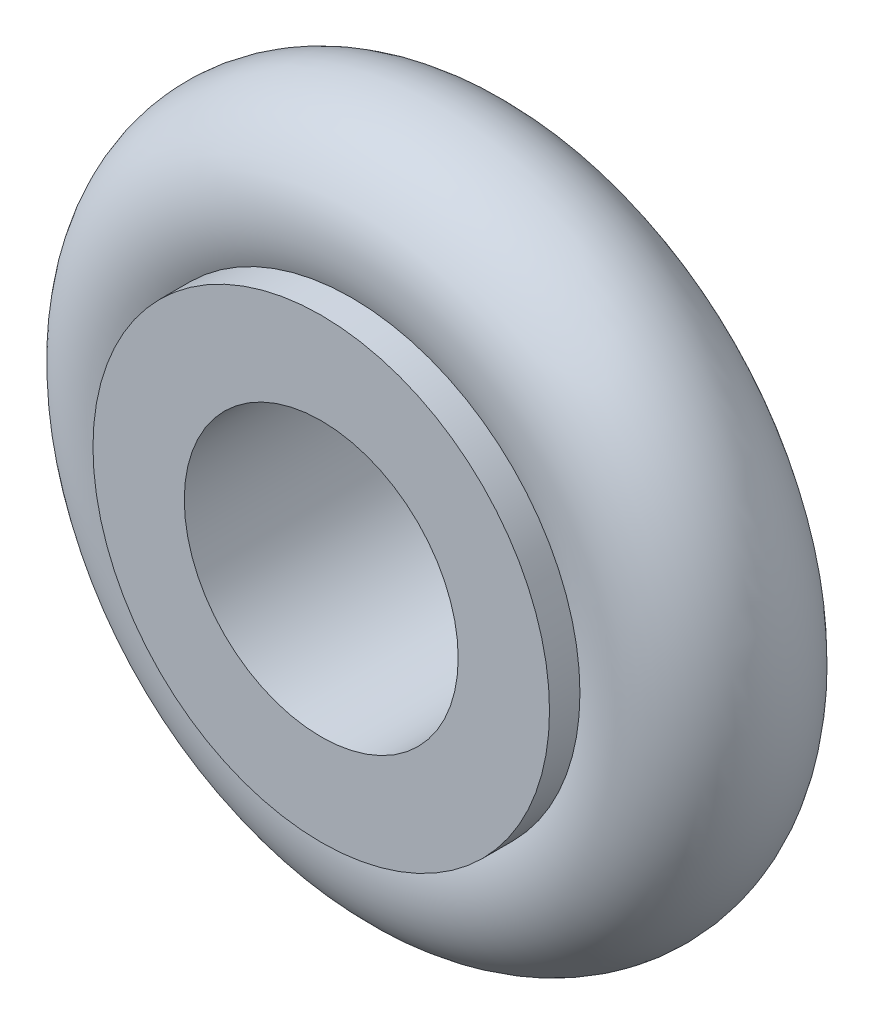
SolidWorks part; units mm, degrees
ref_plane "Alzado" through (0, 0, 0) normal (0, 0, 1) x (1, 0, 0)
ref_plane "Planta" through (0, 0, 0) normal (0, 1, 0) x (1, 0, 0)
ref_plane "Vista lateral" through (0, 0, 0) normal (1, 0, 0) x (0, 0, -1)
sketch "Croquis1" plane through (0, 0, 0) normal (1, 0, 0) x (0, 0, -1)
  line L0 (6.2271, 0) -> (-6.2271, 0) construction
  line L1 (0, 21.5) -> (0, -21.5) construction
  line L2 (-1.9, 0) -> (-1.9, 3.75)
  line L3 (-1.9, 3.75) -> (-1.4, 3.75)
  line L4 (-1.4, 3.75) -> (-1.05, 2.7778)
  line L5 (-1.05, 2.7778) -> (1.05, 2.7778)
  line L6 (1.4, 3.75) -> (1.05, 2.7778)
  line L7 (1.9, 3.75) -> (1.4, 3.75)
  line L8 (1.9, 0) -> (1.9, 3.75)
  line L9 (-1.9, 0) -> (1.9, 0)
  point P4 (0, 0)
  point P8 (0, 0)
  point P18 (0, 2.7778)
  dimension "D1" = 7.5
  dimension "D2" = 3.8
  dimension "D3" = 19.8
  dimension "D4" = 2.1
  dimension "D5" = 0.5
revolve "Revolución1" add sketch "Croquis1" angle 360 about L0
sketch "Croquis5" plane through (0, 0, 0) normal (1, 0, 0) x (0, 0, -1)
  line L0 (-1.05, 2.7778) -> (-1.4, 3.75) construction
  line L1 (-9.0932, 0) -> (9.0932, 0) construction
  circle A0 centre (0, 4.2896) radius 1.5
  point P9 (0, 0)
  dimension "D1" = 3
revolve "Revolución2" add sketch "Croquis5" angle 360 about L1
sketch "Croquis6" plane through (0, 0, 1.9) normal (0, 0, 1) x (1, 0, 0)
  circle A0 centre (0, 0) radius 2.25
  dimension "D1" = 4.5
extrude "Cortar-Extruir3" cut sketch "Croquis6" against normal up to next (3.8 mm away)
sketch "Croquis7" plane through (0, 0, 0) normal (1, 0, 0) x (0, 0, -1)
  line L2 (-1.9, 2.25) -> (1.9, 2.25) construction
  line L3 (-1.05, 2.7778) -> (1.05, 2.7778) construction
  dimension "D1" = 0.5278
sketch "Croquis8" plane through (0, 0, 0) normal (0, 0, 1) x (1, 0, 0)
  circle A0 centre (0, 0) radius 4.2896 construction
  dimension "D1" = 8.5791
